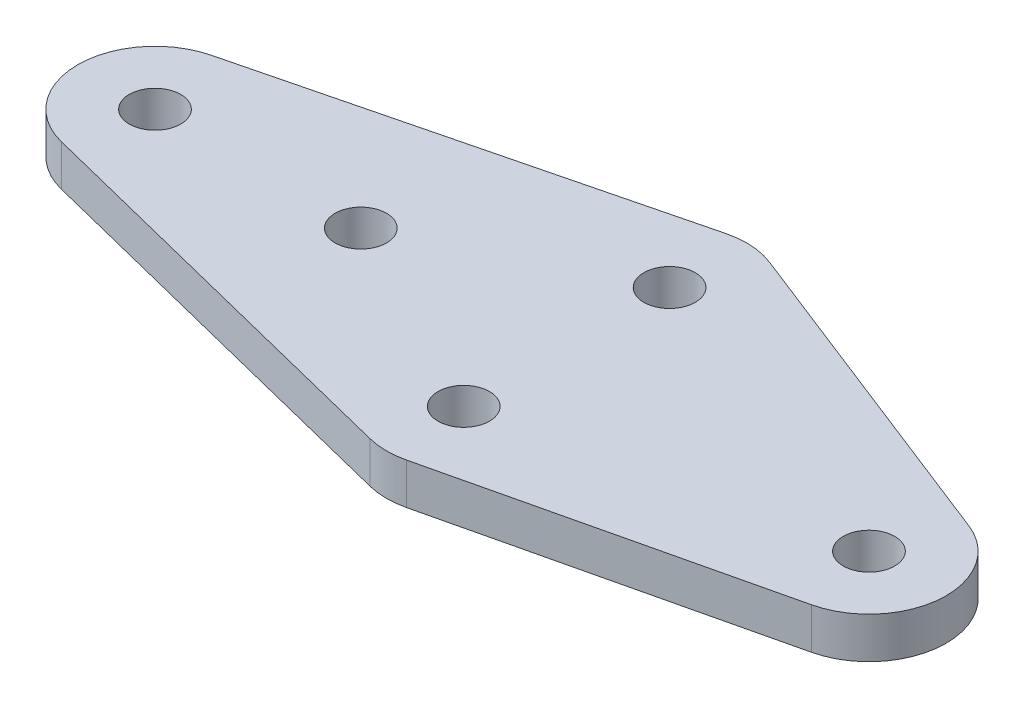
SolidWorks part; units mm, degrees
material "Thornel VCB-20 Carbon Cloth"
ref_plane "Front Plane" through (0, 0, 0) normal (0, 0, 1) x (1, 0, 0)
ref_plane "Top Plane" through (0, 0, 0) normal (0, 1, 0) x (1, 0, 0)
ref_plane "Right Plane" through (0, 0, 0) normal (1, 0, 0) x (0, 0, -1)
sketch "Sketch1" plane through (0, 0, 0) normal (0, 1, 0) x (1, 0, 0)
  line L0 (-37.7566, 7.2761) -> (2.2434, 17.2761)
  line L1 (-37.7566, -7.2761) -> (2.2434, -17.2761)
  line L2 (6.8006, 16.9823) -> (38.6757, 4.4823)
  line L3 (5.7802, -17.3006) -> (37.6553, -9.8006)
  circle A0 centre (35.9376, -2.5) radius 2.5
  arc A1 (6.8006, 16.9823) -> (2.2434, 17.2761) centre (4.0624, 10) ccw
  arc A2 (5.7802, -17.3006) -> (2.2434, -17.2761) centre (4.0624, -10) cw
  arc A3 (-37.7566, -7.2761) -> (-37.7566, 7.2761) centre (-35.9376, 0) cw
  circle A4 centre (4.0624, 10) radius 2.5
  circle A5 centre (4.0624, -10) radius 2.5
  circle A6 centre (-15.9376, 0) radius 2.5
  circle A7 centre (-35.9376, 0) radius 2.5
  arc A8 (37.6553, -9.8006) -> (38.6757, 4.4823) centre (35.9376, -2.5) ccw
  dimension "D1" = 7.5
extrude "Boss-Extrude1" add sketch "Sketch1" along normal blind 4
